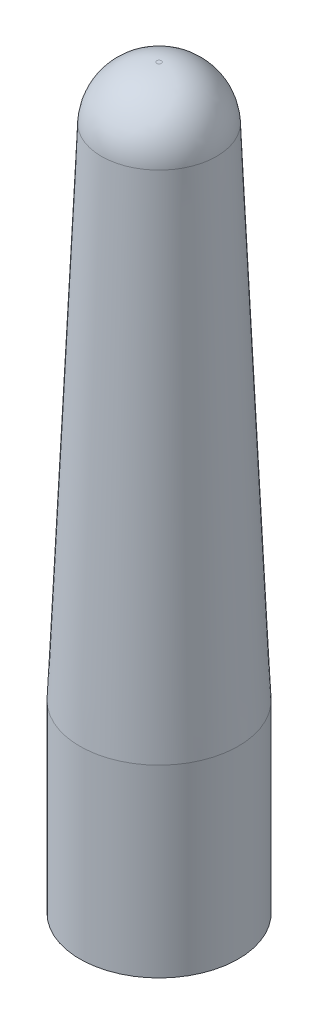
SolidWorks part; units mm, degrees
ref_plane "Front Plane" through (0, 0, 0) normal (0, 0, 1) x (1, 0, 0)
ref_plane "Top Plane" through (0, 0, 0) normal (0, 1, 0) x (1, 0, 0)
ref_plane "Right Plane" through (0, 0, 0) normal (1, 0, 0) x (0, 0, -1)
sketch "Sketch1" plane through (0, 0, 0) normal (0, 0, 1) x (1, 0, 0)
  line L0 (0, 0) -> (0, 38.1)
  line L1 (0, 38.1) -> (3.81, 38.1)
  line L2 (3.81, 38.1) -> (5.461, 0)
  line L3 (5.461, 0) -> (0, 0)
  dimension "D1" = 5.461
  dimension "D2" = 3.81
  dimension "D3" = 38.1
revolve "Revolve1" add sketch "Sketch1" angle 360 about L0
sketch "Sketch2" plane through (0, 0, 0) normal (0, -1, 0) x (-1, 0, 0)
  circle A0 centre (0, 0) radius 5.461
  dimension "D1" = 10.922
extrude "Boss-Extrude1" add sketch "Sketch2" along normal blind 12.7
fillet "Fillet1" radius 3.81 1 edges at (0, 38.1, -3.81)
